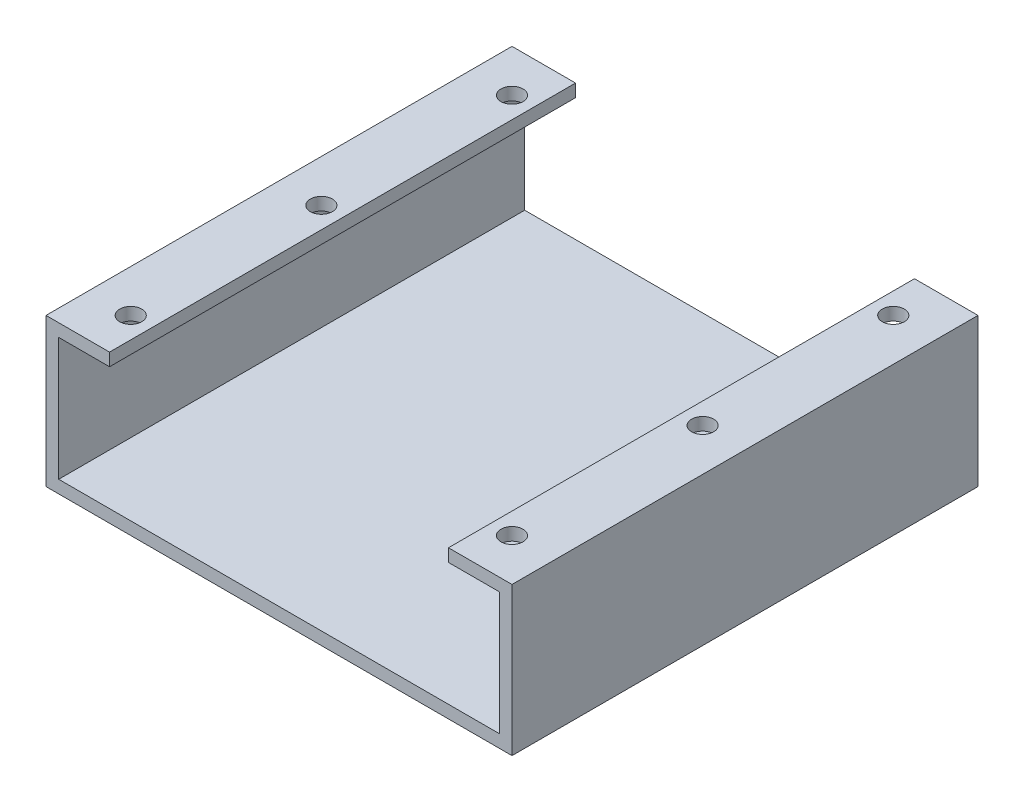
SolidWorks part; units mm, degrees
ref_plane "前视基准面" through (0, 0, 0) normal (0, 0, 1) x (1, 0, 0)
ref_plane "上视基准面" through (0, 0, 0) normal (0, 1, 0) x (1, 0, 0)
ref_plane "右视基准面" through (0, 0, 0) normal (1, 0, 0) x (0, 0, -1)
sketch "草图1" plane through (0, 0, 0) normal (0, 0, 1) x (1, 0, 0)
  line L0 (0, 0) -> (110, 0)
  line L1 (110, 0) -> (110, 35)
  line L2 (110, 35) -> (95, 35)
  line L3 (95, 35) -> (95, 32)
  line L4 (0, 0) -> (0, 35)
  line L5 (0, 35) -> (15, 35)
  line L6 (15, 35) -> (15, 32)
  line L7 (15, 32) -> (3, 32)
  line L8 (3, 32) -> (3, 3)
  line L9 (3, 3) -> (107, 3)
  line L10 (107, 3) -> (107, 32)
  line L11 (107, 32) -> (95, 32)
  point P13 (0, 0)
  point P14 (0, 0)
  point P15 (0, 0)
  point P16 (0, 0)
  point P17 (0, 0)
  point P18 (0, 0)
extrude "凸台-拉伸1" add sketch "草图1" along normal blind 110
sketch "草图2" plane through (0, 35, 0) normal (0, 1, 0) x (1, 0, 0)
  circle A0 centre (10, -10) radius 2.6
  circle A1 centre (100, -10) radius 2.6
  circle A2 centre (100, -55) radius 2.6
  circle A3 centre (100, -100) radius 2.6
  circle A4 centre (10, -55) radius 2.6
  circle A5 centre (10, -100) radius 2.6
  dimension "D1" = 2
  dimension "D2" = 3
extrude "切除-拉伸1" cut sketch "草图2" against normal blind 3
